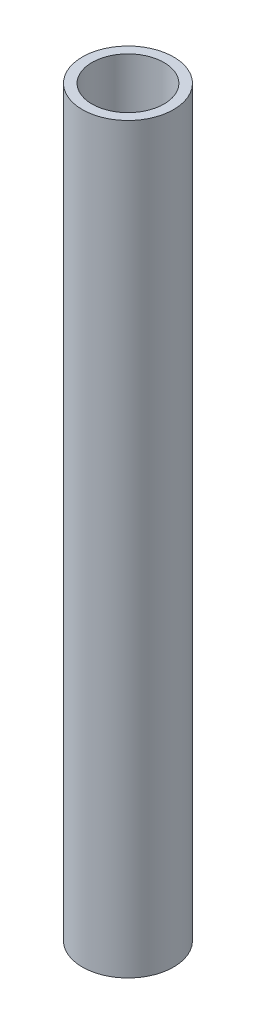
SolidWorks part; units mm, degrees
ref_plane "Front Plane" through (0, 0, 0) normal (0, 0, 1) x (1, 0, 0)
ref_plane "Top Plane" through (0, 0, 0) normal (0, 1, 0) x (1, 0, 0)
ref_plane "Right Plane" through (0, 0, 0) normal (1, 0, 0) x (0, 0, -1)
sketch "Sketch1" plane through (0, 0, 0) normal (0, 1, 0) x (1, 0, 0)
  circle A0 centre (0, 0) radius 24.13
  circle A1 centre (0, 0) radius 19.05
  dimension "D1" = 48.26
  dimension "D2" = 38.1
extrude "Boss-Extrude1" add sketch "Sketch1" along normal mid plane 392.684
